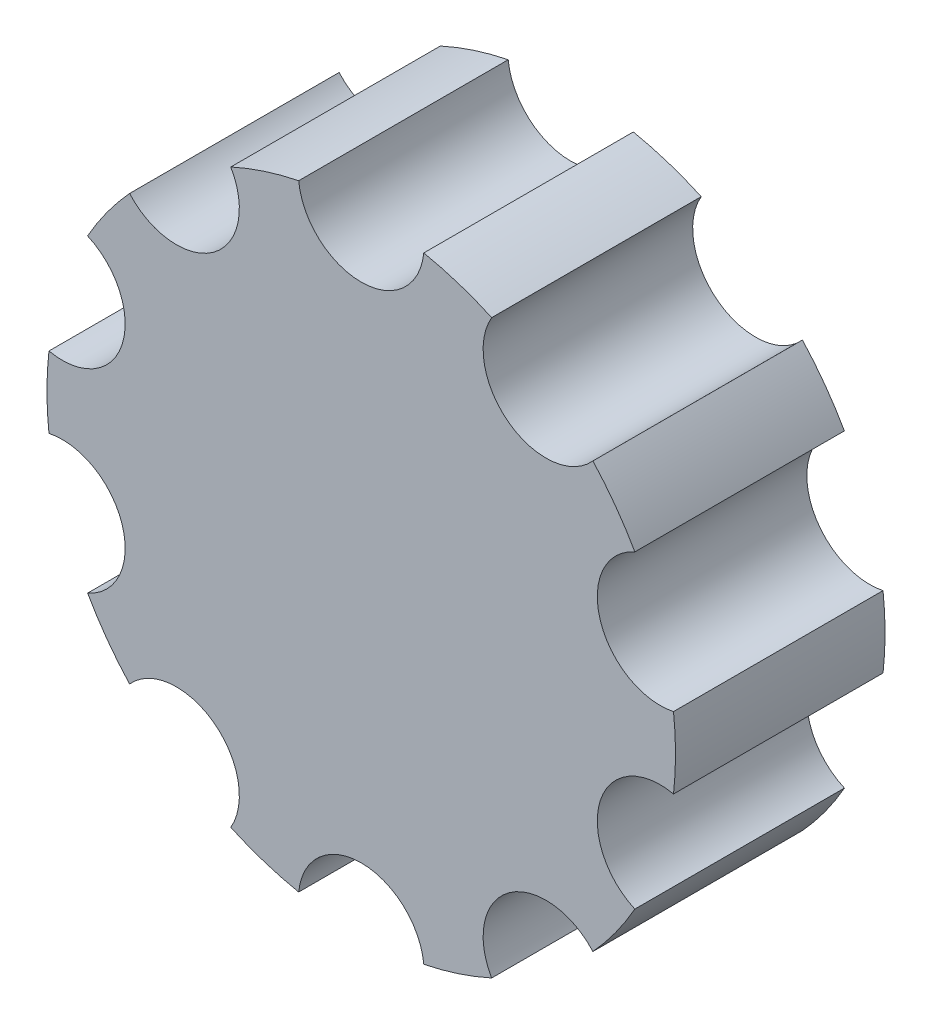
SolidWorks part; units mm, degrees
ref_plane "Front Plane" through (0, 0, 0) normal (0, 0, 1) x (1, 0, 0)
ref_plane "Top Plane" through (0, 0, 0) normal (0, 1, 0) x (1, 0, 0)
ref_plane "Right Plane" through (0, 0, 0) normal (1, 0, 0) x (0, 0, -1)
sketch "Sketch1" plane through (0, 0, 0) normal (0, 0, 1) x (1, 0, 0)
  circle A0 centre (0, 0) radius 7.5
  dimension "D1" = 15
extrude "Boss-Extrude1" add sketch "Sketch1" along normal blind 5
sketch "Sketch3" plane through (0, 0, 5) normal (0, 0, 1) x (1, 0, 0)
  circle A0 centre (0, 7.5) radius 1.5
  circle A1 centre (0, 0) radius 7.5 construction
  circle A2 centre (4.4084, 6.0676) radius 1.5
  circle A3 centre (7.1329, 2.3176) radius 1.5
  circle A4 centre (7.1329, -2.3176) radius 1.5
  circle A5 centre (4.4084, -6.0676) radius 1.5
  circle A6 centre (0, -7.5) radius 1.5
  circle A7 centre (-4.4084, -6.0676) radius 1.5
  circle A8 centre (-7.1329, -2.3176) radius 1.5
  circle A9 centre (-7.1329, 2.3176) radius 1.5
  circle A10 centre (-4.4084, 6.0676) radius 1.5
  point P25 (0, 0)
  dimension "D1" = 3
  dimension "D2" = 10
extrude "Cut-Extrude1" cut sketch "Sketch3" along direction (0, 0, 1) on the side against the normal up to surface (5 mm away)
